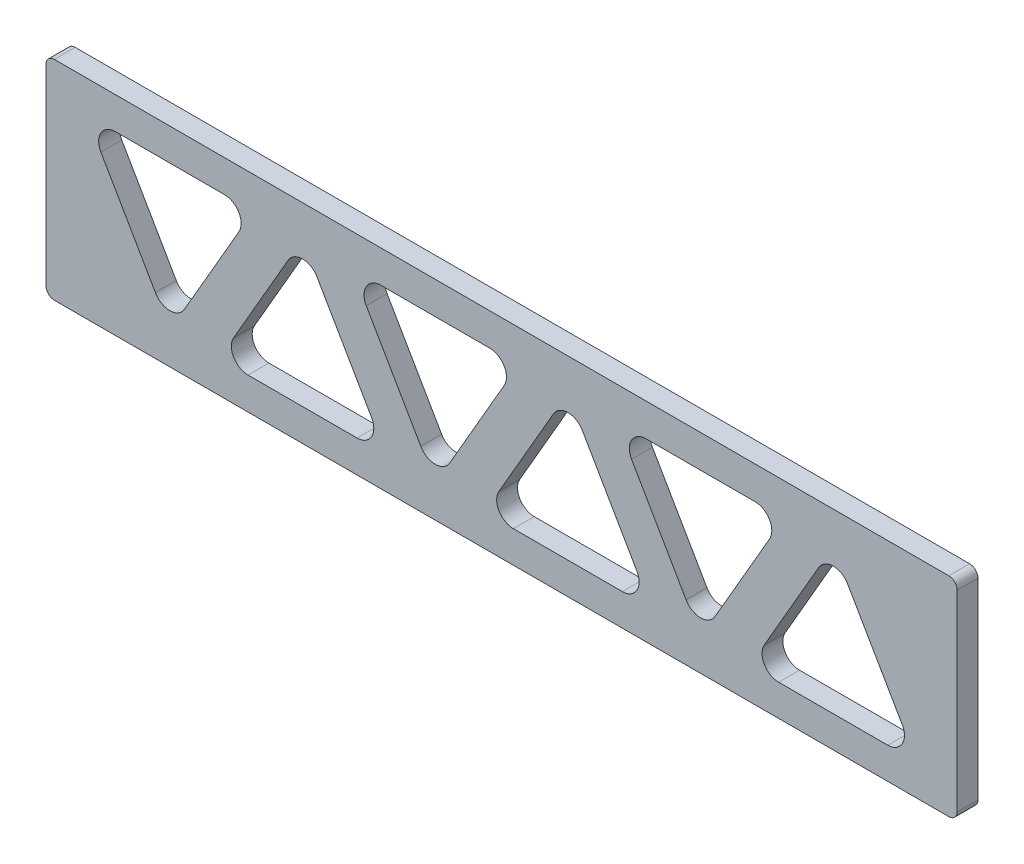
SolidWorks part; units mm, degrees
material "ABS PC"
ref_plane "Front Plane" through (0, 0, 0) normal (0, 0, 1) x (1, 0, 0)
ref_plane "Top Plane" through (0, 0, 0) normal (0, 1, 0) x (1, 0, 0)
ref_plane "Right Plane" through (0, 0, 0) normal (1, 0, 0) x (0, 0, -1)
sketch "Sketch2" plane through (0, 0, 0) normal (0, 0, 1) x (1, 0, 0)
  line L0 (-5.1244, 14.6538) -> (267.1636, 14.6538)
  line L1 (269.7036, 17.1938) -> (269.7036, 75.6138)
  line L2 (267.1636, 78.1538) -> (-5.1244, 78.1538)
  line L3 (-7.6644, 75.6138) -> (-7.6644, 17.1938)
  line L4 (30.0546, 24.4068) -> (30.0546, 68.4009) construction
  line L5 (-7.6644, 46.4038) -> (269.7036, 46.4038) construction
  line L6 (30.0546, 24.4068) -> (4.6546, 68.4009)
  line L7 (55.4546, 68.4009) -> (4.6546, 68.4009)
  line L8 (55.4546, 68.4009) -> (30.0546, 24.4068)
  line L9 (70.4406, 68.4009) -> (95.8406, 24.4068)
  line L10 (45.0406, 24.4068) -> (95.8406, 24.4068)
  line L11 (45.0406, 24.4068) -> (70.4406, 68.4009)
  line L12 (70.4406, 24.4068) -> (70.4406, 68.4009)
  line L13 (110.8263, 24.3058) -> (85.4263, 68.2999)
  line L14 (136.2263, 68.2999) -> (85.4263, 68.2999)
  line L15 (136.2263, 68.2999) -> (110.8263, 24.3058)
  line L16 (125.8123, 24.3058) -> (151.2123, 68.2999)
  line L17 (151.2123, 68.2999) -> (176.6123, 24.3058)
  line L18 (125.8123, 24.3058) -> (176.6123, 24.3058)
  line L19 (191.5979, 24.2049) -> (166.1979, 68.199)
  line L20 (216.9979, 68.199) -> (166.1979, 68.199)
  line L21 (216.9979, 68.199) -> (191.5979, 24.2049)
  line L22 (206.5839, 24.2049) -> (231.9839, 68.199)
  line L23 (231.9839, 68.199) -> (257.3839, 24.2049)
  line L24 (206.5839, 24.2049) -> (257.3839, 24.2049)
  arc A0 (267.1636, 14.6538) -> (269.7036, 17.1938) centre (267.1636, 17.1938) ccw
  arc A1 (269.7036, 75.6138) -> (267.1636, 78.1538) centre (267.1636, 75.6138) ccw
  arc A2 (-5.1244, 14.6538) -> (-7.6644, 17.1938) centre (-5.1244, 17.1938) cw
  arc A3 (-5.1244, 78.1538) -> (-7.6644, 75.6138) centre (-5.1244, 75.6138) ccw
  point P0 (30.0546, 46.4038)
  point P15 (70.4406, 46.4038)
  point P30 (269.7036, 14.6538)
  point P33 (269.7036, 78.1538)
  point P36 (-7.6644, 14.6538)
  point P39 (-7.6644, 78.1538)
  dimension "D28" = 2.54
  dimension "D1" = 63.5
  dimension "D2" = 277.368
  dimension "D3" = 50.8
  dimension "D4" = 50.8
  dimension "D5" = 50.8
  dimension "D6" = 21.997
  dimension "D7" = 90
  dimension "D8" = 270
  dimension "D9" = 300
  dimension "D10" = 300
  dimension "D11" = 0
  dimension "D13" = 14.986
  dimension "D14" = 14.986
  dimension "D15" = 50.8
  dimension "D16" = 50.8
  dimension "D17" = 50.8
  dimension "D18" = 50.8
  dimension "D19" = 50.8
  dimension "D20" = 300
  dimension "D21" = 12.319
  dimension "D22" = 9.652
  dimension "D23" = 63.5
  dimension "D24" = 270
  dimension "D25" = 9.753
  dimension "D26" = 9.753
  dimension "D27" = 12.3197
  dimension "D12" = 3
extrude "Boss-Extrude1" add sketch "Sketch2" along normal blind 6.35 contours L2 L3 L0 L1 L24 L22 L23 L18 L16 L17 L7 L8 L6 L10 L11 L9 L14 L15 L13 L20 L21 L19
fillet "Fillet1" radius 5.08 18 edges at (30.0546, 24.4068, 3.175) (191.5979, 24.2049, 3.175) (110.8263, 24.3058, 3.175) (151.2123, 68.2999, 3.175) (231.9839, 68.199, 3.175) (166.1979, 68.199, 3.175) (85.4263, 68.2999, 3.175) (206.5839, 24.2049, 3.175) (125.8123, 24.3058, 3.175) (45.0406, 24.4068, 3.175) (257.3839, 24.2049, 3.175) (176.6123, 24.3058, 3.175) (95.8406, 24.4068, 3.175) (70.4406, 68.4009, 3.175) (4.6546, 68.4009, 3.175) (55.4546, 68.4009, 3.175) (136.2263, 68.2999, 3.175) (216.9979, 68.199, 3.175)
